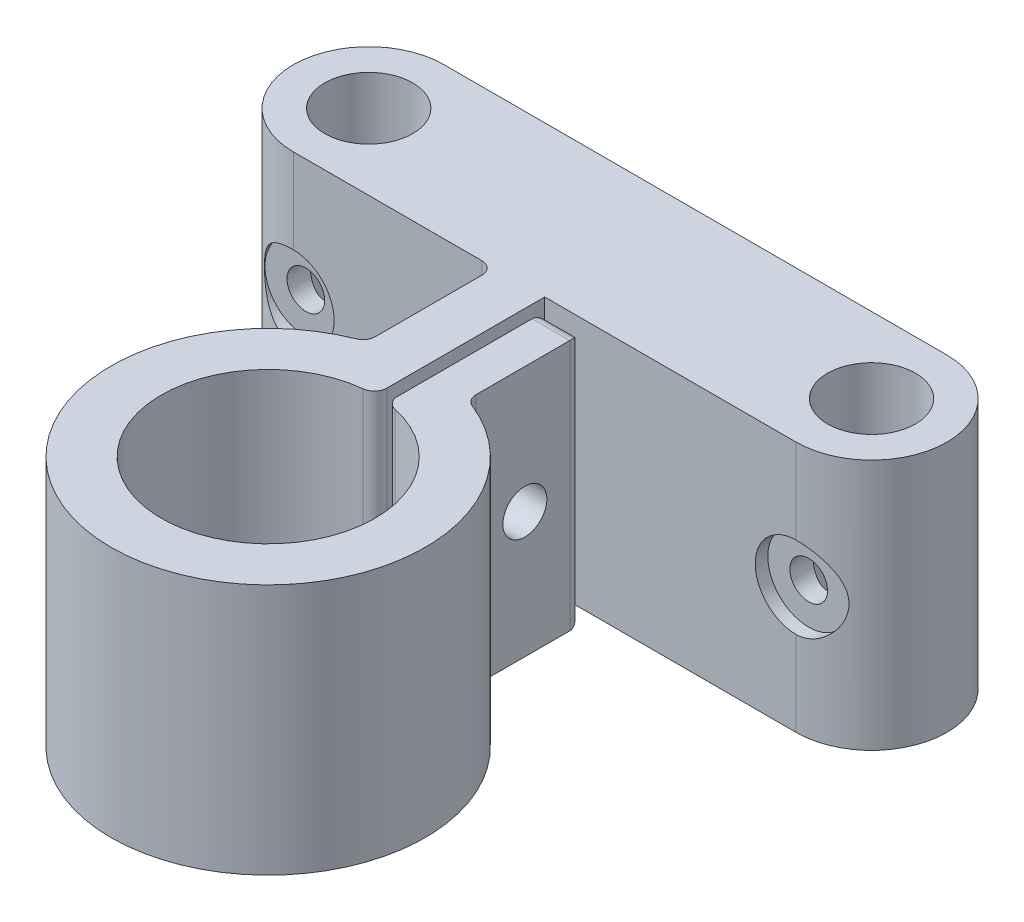
SolidWorks part; units mm, degrees
ref_plane "Alzado" through (0, 0, 0) normal (0, 0, 1) x (1, 0, 0)
ref_plane "Planta" through (0, 0, 0) normal (0, 1, 0) x (1, 0, 0)
ref_plane "Vista lateral" through (0, 0, 0) normal (1, 0, 0) x (0, 0, -1)
sketch "Croquis1" plane through (0, 0, 0) normal (0, 1, 0) x (1, 0, 0)
  line L0 (-20, 6) -> (20, 6)
  line L1 (0, -55) -> (0, 55) construction
  line L2 (20, -6) -> (-20, -6)
  line L3 (-55, 0) -> (55, 0) construction
  arc A0 (20, 6) -> (20, -6) centre (20, 0) cw
  arc A1 (-20, 6) -> (-20, -6) centre (-20, 0) ccw
  point P0 (-26, 0)
  point P7 (0, 6)
  point P10 (0, -6)
  dimension "D1" = 40
  dimension "D2" = 6
extrude "Saliente-Extruir1" add sketch "Croquis1" along normal blind 20
sketch "Croquis2" plane through (0, 0, 0) normal (0, 1, 0) x (1, 0, 0)
  line L0 (-11, 0) -> (11, 0) construction
  circle A0 centre (-20, 0) radius 3.5
  circle A1 centre (20, 0) radius 3.5
  arc A2 (-20, 6) -> (-20, -6) centre (-20, 0) ccw construction
  arc A3 (20, -6) -> (20, 6) centre (20, 0) ccw construction
  dimension "D1" = 7
extrude "Cortar-Extruir1" cut sketch "Croquis2" along normal through all
sketch "Croquis3" plane through (0, 0, 0) normal (0, 0, 1) x (1, 0, 0)
  line L0 (-20, 20) -> (-20, 0) construction
  line L1 (0, -6.6) -> (0, 6.6) construction
  circle A0 centre (-20, 10) radius 1.5
  circle A1 centre (20, 10) radius 1.5
  dimension "D1" = 3
extrude "Cortar-Extruir2" cut sketch "Croquis3" against normal through all both and the other way through all
sketch "Croquis4" plane through (0, 0, 6) normal (0, 0, 1) x (1, 0, 0)
  line L0 (0, -6.6) -> (0, 6.6) construction
  circle A0 centre (-20, 10) radius 3.25
  circle A1 centre (20, 10) radius 3.25
  dimension "D1" = 6.5
extrude "Cortar-Extruir3" cut sketch "Croquis4" against normal blind 1
sketch "Croquis6" plane through (0, 0, 0) normal (0, -1, 0) x (1, 0, 0)
  line L0 (0, -6.6) -> (0, 6.6) construction
  line L1 (-4, 6) -> (-4, 16.1573)
  line L2 (-20, 6) -> (20, 6) construction
  line L3 (-4, 6) -> (0, 6)
  line L4 (4, 7) -> (4, 16.1573)
  line L5 (0, 6) -> (0, 19.5)
  line L6 (1, 7) -> (1, 19.559)
  line L7 (1, 7) -> (4, 7)
  arc A0 (1, 19.559) -> (0, 19.5) centre (0, 28) ccw
  arc A1 (4, 16.1573) -> (-4, 16.1573) centre (0, 28) ccw
  point P1 (4, 6)
  point P5 (4, 6)
  point P15 (1, 7.0784)
  point P16 (0, 0)
  dimension "D1" = 17
  dimension "D2" = 25
  dimension "D3" = 4
  dimension "D4" = 22
  dimension "D5" = 1
  dimension "D6" = 3
  dimension "D7" = 1
extrude "Saliente-Extruir2" add sketch "Croquis6" against normal up to surface (20 mm away) up to face at (-20, 20, 3.5)
sketch "Croquis7" plane through (0, 0, 0) normal (1, 0, 0) x (0, 0, -1)
  line L0 (-11.5786, 20) -> (-11.5786, 0) construction
  line L1 (-16.1573, 20) -> (-7, 20) construction
  line L2 (6.6, 0) -> (-6.6, 0) construction
  circle A0 centre (-11.5786, 10) radius 1.75
  point P2 (0, 0)
  point P9 (-10.4689, 10.3886)
  point P10 (-11.5786, 10)
  dimension "D1" = 3.5
extrude "Cortar-Extruir4" cut sketch "Croquis7" against normal through all both and the other way through all
sketch "Croquis8" plane through (-4, 0, 0) normal (-1, 0, 0) x (0, 0, 1)
  line L1 (11.5786, 13.7528) -> (8.3286, 11.8764)
  line L2 (8.3286, 11.8764) -> (8.3286, 8.1236)
  line L3 (8.3286, 8.1236) -> (11.5786, 6.2472)
  line L4 (11.5786, 6.2472) -> (14.8286, 8.1236)
  line L5 (14.8286, 8.1236) -> (14.8286, 11.8764)
  line L6 (14.8286, 11.8764) -> (11.5786, 13.7528)
  circle A0 centre (11.5786, 10) radius 3.25 construction
  dimension "D1" = 6.5
extrude "Cortar-Extruir5" cut sketch "Croquis8" against normal blind 2
fillet "Redondeo1" radius 1 9 edges at (1, 10, 7) (2.5, 20, 7) (2.5, 0, 7) (4, 10, 7) (-4, 10, 16.1573) (-4, 10, 6) (4, 10, 16.1573) (1, 10, 19.559) (0, 10, 19.5)
